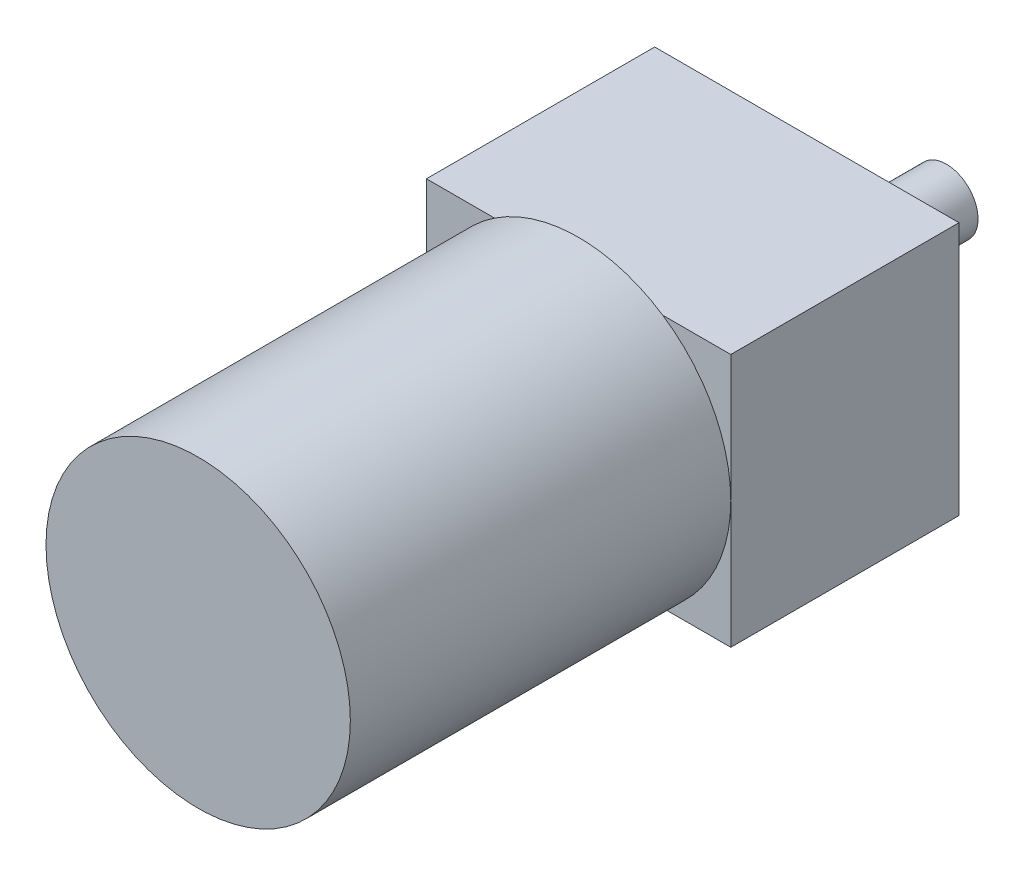
SolidWorks part; units mm, degrees
ref_plane "Front Plane" through (0, 0, 0) normal (0, 0, 1) x (1, 0, 0)
ref_plane "Top Plane" through (0, 0, 0) normal (0, 1, 0) x (1, 0, 0)
ref_plane "Right Plane" through (0, 0, 0) normal (1, 0, 0) x (0, 0, -1)
sketch "Sketch1" plane through (0, 0, 0) normal (0, 0, 1) x (1, 0, 0)
  line L1 (0, 0) -> (12, 0)
  line L2 (0, 0) -> (0, -10)
  line L3 (0, -10) -> (12, -10)
  line L4 (12, 0) -> (12, -10)
extrude "Boss-Extrude1" add sketch "Sketch1" along normal blind 9
sketch "Sketch2" plane through (0, 0, 9) normal (0, 0, 1) x (1, 0, 0)
  circle A0 centre (6, -5) radius 6
extrude "Boss-Extrude2" add sketch "Sketch2" along normal blind 15
sketch "Sketch3" plane through (0, 0, 0) normal (0, 0, -1) x (-1, 0, 0)
  circle A0 centre (-6, -5) radius 2
extrude "Boss-Extrude3" add sketch "Sketch3" along normal blind 1
sketch "Sketch4" plane through (0, 0, -1) normal (0, 0, -1) x (-1, 0, 0)
  circle A0 centre (-6, -5) radius 1.25
extrude "Boss-Extrude4" add sketch "Sketch4" along normal blind 4.5
